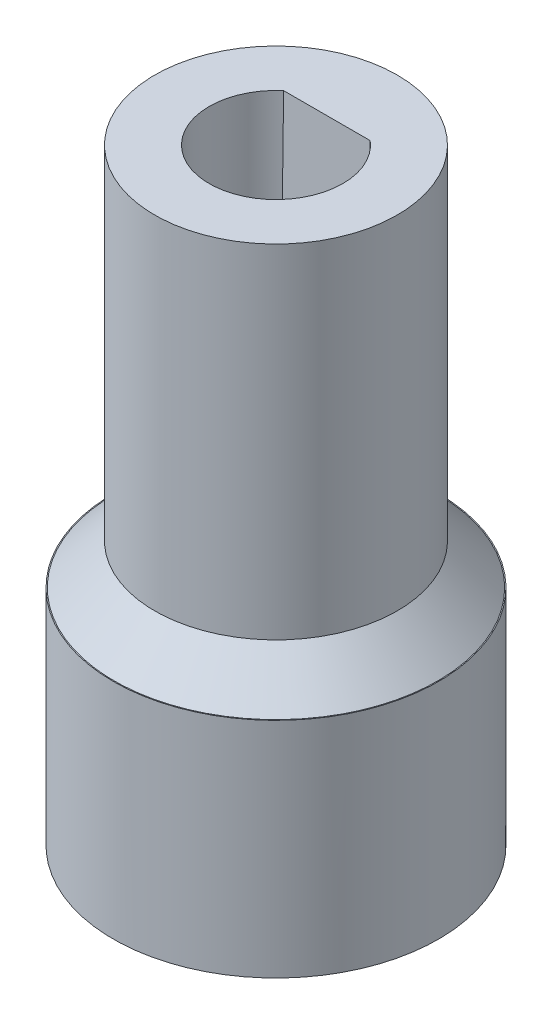
SolidWorks part; units mm, degrees
ref_plane "Front Plane" through (0, 0, 0) normal (0, 0, 1) x (1, 0, 0)
ref_plane "Top Plane" through (0, 0, 0) normal (0, 1, 0) x (1, 0, 0)
ref_plane "Right Plane" through (0, 0, 0) normal (1, 0, 0) x (0, 0, -1)
sketch "Sketch1" plane through (0, 0, 0) normal (0, 1, 0) x (1, 0, 0)
  circle A0 centre (0, 0) radius 7.62
  dimension "D1" = 15.24
extrude "Boss-Extrude1" add sketch "Sketch1" along normal blind 38.1
sketch "Sketch2" plane through (0, 38.1, 0) normal (0, 1, 0) x (1, 0, 0)
  line L0 (0, 0) -> (0, 3) construction
  line L1 (-2.6458, 3) -> (2.6458, 3) construction
  line L3 (-2.7203, 3.2) -> (2.7203, 3.2)
  arc A0 (-2.6458, 3) -> (2.6458, 3) centre (0, 0) ccw construction
  arc A2 (-2.7203, 3.2) -> (2.7203, 3.2) centre (0, 0) ccw
  dimension "D1" = 8
  dimension "D2" = 3
  dimension "D3" = 0.2
sketch "Sketch3" plane through (0, 0, 0) normal (0, -1, 0) x (1, 0, 0)
  circle A0 centre (0, 0) radius 6.45
  dimension "D1" = 12.9
ref_plane "Plane1" through (0, 19.1, 0) normal (0, 1, 0) x (1, 0, 0)
sketch "Sketch4" plane through (0, 19.1, 0) normal (0, 1, 0) x (1, 0, 0)
  line L0 (-2.6458, 3) -> (2.6458, 3) construction
  line L1 (-2.569, 2.8) -> (2.569, 2.8)
  arc A0 (-2.6458, 3) -> (2.6458, 3) centre (0, 0) ccw construction
  arc A1 (-2.569, 2.8) -> (2.569, 2.8) centre (0, 0) ccw
  dimension "D1" = 0.2
loft "Motor Shaft Couple" cut profiles "Sketch4", "Sketch2"
ref_plane "Plane2" through (0, 14.02, 0) normal (0, 1, 0) x (1, 0, 0)
sketch "Sketch5" plane through (0, 14.02, 0) normal (0, 1, 0) x (1, 0, 0)
  circle A0 centre (0, 0) radius 6.096
  dimension "D1" = 12.192
loft "Dowel Couple" cut profiles "Sketch5", "Sketch3"
sketch "Sketch6" plane through (0, 0, 0) normal (0, -1, 0) x (1, 0, 0)
  circle A0 centre (0, 0) radius 10.218
  circle A1 centre (0, 0) radius 7.62
  dimension "D1" = 20.4361
  dimension "D2" = 15.24
extrude "Boss-Extrude2" add sketch "Sketch6" against normal up to surface (14.02 mm away) up to face at (0, 14.02, 6.096)
chamfer "Chamfer1" distance 2.54 angle 45 1 edges at (0, 14.02, 7.62)
equation "\"D1@Sketch3\"=0.5in + 0.2mm"
